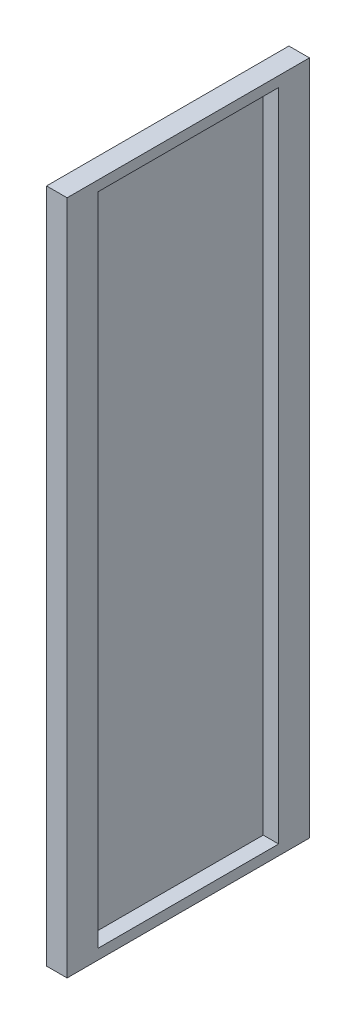
SolidWorks part; units mm, degrees
ref_plane "Front Plane" through (0, 0, 0) normal (0, 0, 1) x (1, 0, 0)
ref_plane "Top Plane" through (0, 0, 0) normal (0, 1, 0) x (1, 0, 0)
ref_plane "Right Plane" through (0, 0, 0) normal (1, 0, 0) x (0, 0, -1)
sketch "Sketch1" plane through (0, 0, 0) normal (0, 1, 0) x (1, 0, 0)
  line L1 (12.7, -149.86) -> (-12.7, -149.86)
  line L2 (12.7, -149.86) -> (12.7, 149.86)
  line L3 (12.7, 149.86) -> (-12.7, 149.86)
  line L4 (-12.7, -149.86) -> (-12.7, 149.86)
  line L5 (12.7, -149.86) -> (-12.7, 149.86) construction
  line L6 (12.7, 149.86) -> (-12.7, -149.86) construction
  point P0 (0, 0)
  dimension "D1" = 25.4
  dimension "D2" = 299.72
extrude "Boss-Extrude1" add sketch "Sketch1" along normal mid plane 835.66
sketch "Sketch2" plane through (12.7, 0, 0) normal (1, 0, 0) x (0, 0, -1)
  line L0 (-149.86, 417.83) -> (149.86, 417.83) construction
  line L1 (111.76, -405.13) -> (-111.76, -405.13)
  line L2 (111.76, -405.13) -> (111.76, 405.13)
  line L3 (111.76, 405.13) -> (-111.76, 405.13)
  line L4 (-111.76, -405.13) -> (-111.76, 405.13)
  line L5 (111.76, -405.13) -> (-111.76, 405.13) construction
  line L6 (111.76, 405.13) -> (-111.76, -405.13) construction
  line L7 (-149.86, 417.83) -> (-149.86, -417.83) construction
  point P0 (0, 0)
  dimension "D1" = 12.7
  dimension "D2" = 38.1
extrude "Cut-Extrude1" cut sketch "Sketch2" against normal blind 19.05
sketch "Sketch3" plane through (-12.7, 0, 0) normal (-1, 0, 0) x (0, 0, 1)
  line L0 (-149.86, 417.83) -> (149.86, 417.83) construction
  line L1 (-143.51, 290.83) -> (-118.11, 290.83)
  line L2 (-143.51, 290.83) -> (-143.51, 172.72)
  line L3 (-143.51, 172.72) -> (-118.11, 172.72)
  line L4 (-118.11, 290.83) -> (-118.11, 172.72)
  line L5 (-149.86, 417.83) -> (-149.86, -417.83) construction
  line L6 (-149.86, -417.83) -> (149.86, -417.83) construction
  dimension "D1" = 127
  dimension "D2" = 6.35
  dimension "D3" = 25.4
  dimension "D4" = 590.55
extrude "Cut-Extrude2" cut sketch "Sketch3" against normal blind 12.7
